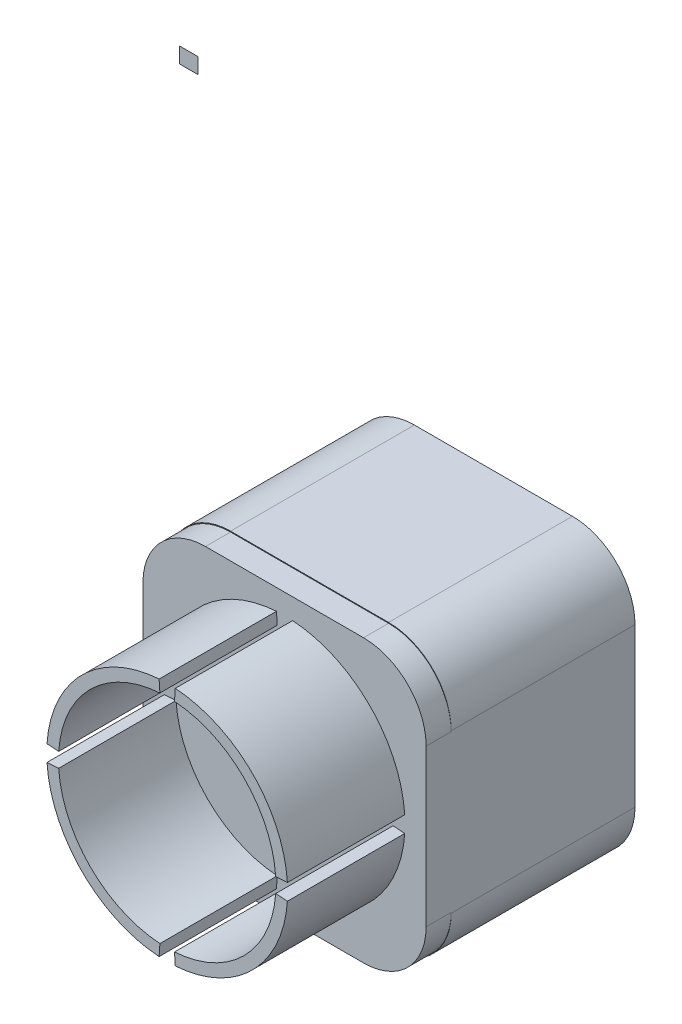
SolidWorks part; units mm, degrees
ref_plane "Front Plane" through (0, 0, 0) normal (0, 0, 1) x (1, 0, 0)
ref_plane "Top Plane" through (0, 0, 0) normal (0, 1, 0) x (1, 0, 0)
ref_plane "Right Plane" through (0, 0, 0) normal (1, 0, 0) x (0, 0, -1)
sketch "Sketch1" plane through (0, 0, 0) normal (0, 0, 1) x (1, 0, 0)
  line L13 (-20.0541, 22.5273) -> (-18.8954, 22.5273)
  line L14 (-20.0541, 22.5273) -> (-20.0541, 21.5306)
  line L15 (-20.0541, 21.5306) -> (-18.8954, 21.5306)
  line L16 (-18.8954, 22.5273) -> (-18.8954, 21.5306)
extrude "Boss-Extrude1" add sketch "Sketch1" along normal blind 0.0005
sketch "Sketch2" plane through (0, 0, 0) normal (0, 0, 1) x (1, 0, 0)
  line L5 (-5.05, 9.05) -> (5.05, 9.05)
  line L6 (-2.5794, 1.43) -> (2.5794, 1.43)
  line L7 (2.5802, -1.4285) -> (-2.5785, -1.4315)
  line L8 (-9.05, 5.05) -> (-9.05, -5.05)
  line L9 (-5.05, -9.05) -> (5.05, -9.05)
  line L10 (9.05, 5.05) -> (9.05, -5.05)
  arc A1 (-2.5794, 1.43) -> (-2.5785, -1.4315) centre (0, 0) ccw
  arc A2 (2.5794, 1.43) -> (2.5802, -1.4285) centre (0, 0) cw
  arc A3 (-9.05, -5.05) -> (-5.05, -9.05) centre (-5.05, -5.05) ccw
  arc A4 (5.05, -9.05) -> (9.05, -5.05) centre (5.05, -5.05) ccw
  arc A5 (5.05, 9.05) -> (9.05, 5.05) centre (5.05, 5.05) cw
  arc A6 (-5.05, 9.05) -> (-9.05, 5.05) centre (-5.05, 5.05) ccw
  dimension "D3" = 1.43
  dimension "D7" = 4
  dimension "D1" = 9.05
  dimension "D2" = 9.05
  dimension "D4" = 1.43
  dimension "D5" = 9.05
  dimension "D6" = 9.05
extrude "Boss-Extrude2" add sketch "Sketch2" along normal blind 11.7499
sketch "Sketch3" plane through (0, 0, 11.7499) normal (0, 0, 1) x (1, 0, 0)
  line L1 (-5.05, 9.0001) -> (5.05, 9.0001)
  line L2 (-9.05, 5.0001) -> (-9.05, -5.0001)
  line L3 (-5.05, -9.0001) -> (5.05, -9.0001)
  line L4 (9.05, 5.0001) -> (9.05, -5.0001)
  line L5 (-9.05, 9.0001) -> (9.05, -9.0001) construction
  line L6 (-9.05, -9.0001) -> (9.05, 9.0001) construction
  arc A0 (-9.05, -5.0001) -> (-5.05, -9.0001) centre (-5.05, -5.0001) ccw
  arc A1 (5.05, -9.0001) -> (9.05, -5.0001) centre (5.05, -5.0001) ccw
  arc A2 (5.05, 9.0001) -> (9.05, 5.0001) centre (5.05, 5.0001) cw
  arc A3 (-5.05, 9.0001) -> (-9.05, 5.0001) centre (-5.05, 5.0001) ccw
  point P0 (0, 0)
  dimension "D2" = 4
  dimension "D1" = 9.05
extrude "Boss-Extrude3" add sketch "Sketch3" along normal blind 1.6
sketch "Sketch4" plane through (0, 0, 13.3499) normal (0, 0, 1) x (1, 0, 0)
  circle A1 centre (0, 0) radius 7.7
  dimension "D2" = 15.4
extrude "Boss-Extrude4" add sketch "Sketch4" along normal blind 7.5
sketch "Sketch5" plane through (0, 0, 13.3499) normal (0, 0, 1) x (1, 0, 0)
  circle A0 centre (0, 0) radius 6.95
  dimension "D1" = 13.9
extrude "Cut-Extrude1" cut sketch "Sketch5" along normal blind 7.5
sketch "Sketch11" plane through (0, 0, 13.3499) normal (0, 0, 1) x (1, 0, 0)
  line L4 (0, 8.1838) -> (-0.55, 8.1838)
  line L5 (-0.55, 8.1838) -> (0, 0)
  line L6 (0, 8.1838) -> (0.55, 8.1838)
  line L7 (0.55, 8.1838) -> (0, 0)
  dimension "D1" = 0.55
  dimension "D2" = 0.55
extrude "Cut-Extrude2" cut sketch "Sketch11" along normal blind 7.5
pattern_circular "CirPattern1" count 4 over 360 about axis through (0, 0, 20.8499) along (0, 0, -1) of "Cut-Extrude2"
